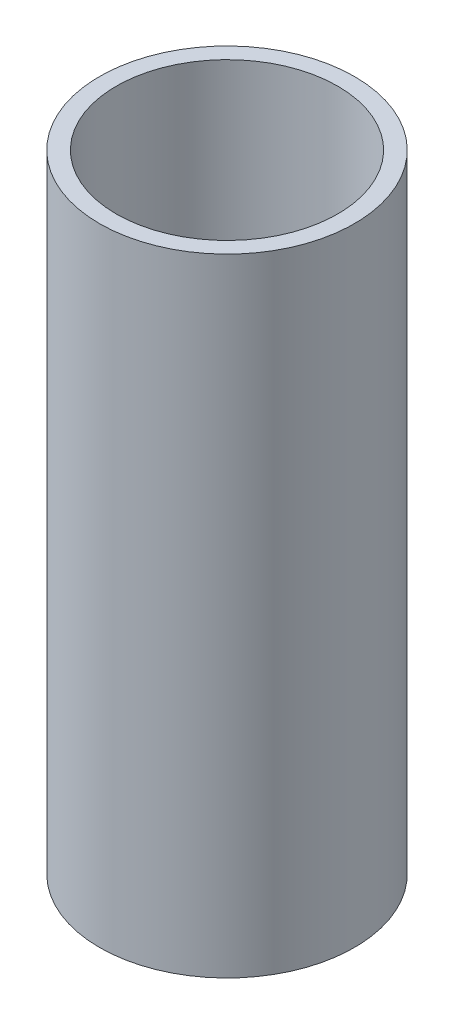
SolidWorks part; units mm, degrees
ref_plane "Front Plane" through (0, 0, 0) normal (0, 0, 1) x (1, 0, 0)
ref_plane "Top Plane" through (0, 0, 0) normal (0, 1, 0) x (1, 0, 0)
ref_plane "Right Plane" through (0, 0, 0) normal (1, 0, 0) x (0, 0, -1)
sketch "Sketch1" plane through (0, 0, 0) normal (0, 1, 0) x (1, 0, 0)
  circle A0 centre (0, 0) radius 30.5
  circle A1 centre (0, 0) radius 26.5
  dimension "D1" = 61
  dimension "D2" = 53
extrude "Boss-Extrude1" add sketch "Sketch1" along normal blind 150
